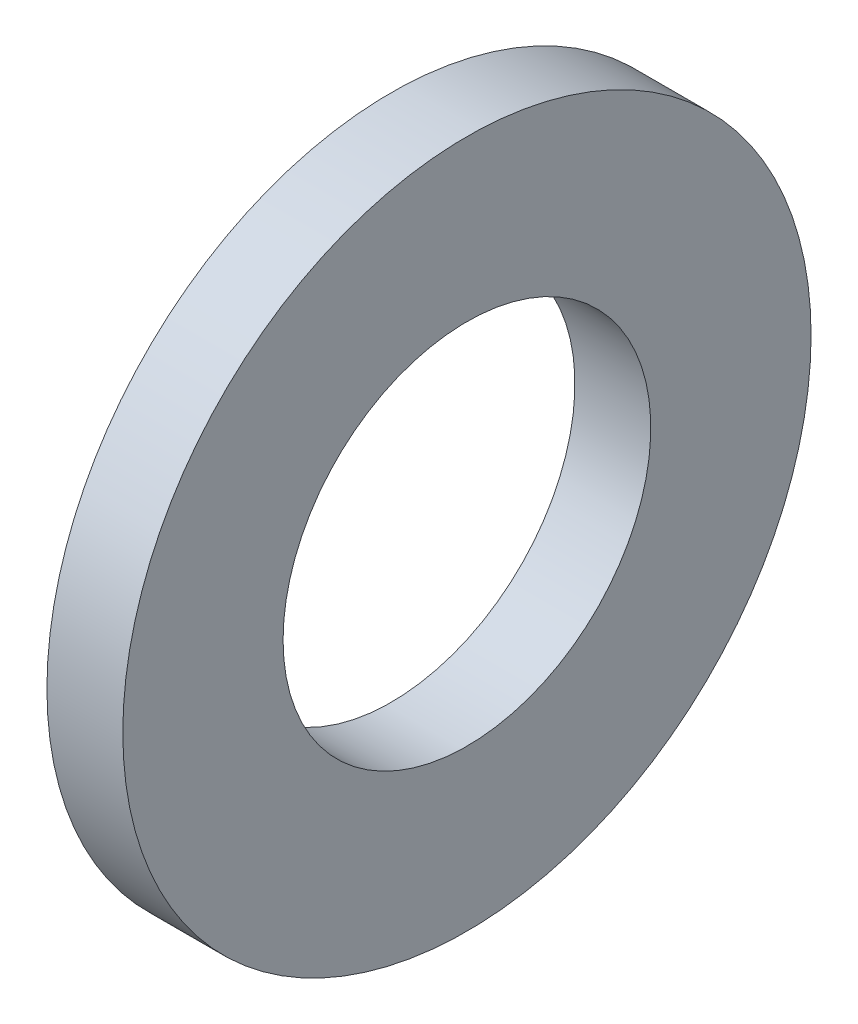
SolidWorks part; units mm, degrees
ref_plane "Plane1" through (0, 0, 0) normal (0, 0, 1) x (1, 0, 0)
ref_plane "Plane2" through (0, 0, 0) normal (0, 1, 0) x (1, 0, 0)
ref_plane "Plane3" through (0, 0, 0) normal (1, 0, 0) x (0, 0, -1)
sketch "Sketch1" plane through (0, 0, 0) normal (0, 0, 1) x (1, 0, 0)
  line L0 (-34.925, 0) -> (9.525, 0) construction
  line L1 (0, 6.785) -> (0, 12.7)
  line L2 (0, 12.7) -> (-2.8, 12.7)
  line L3 (-2.8, 12.7) -> (-2.8, 6.785)
  line L4 (-2.8, 6.785) -> (0, 6.785)
  dimension "Thickness" = 2.8
  dimension "Inside_dia" = 13.57
  dimension "Outside_dia" = 25.4
revolve "Base-Revolve" add sketch "Sketch1" angle 360 about L0
